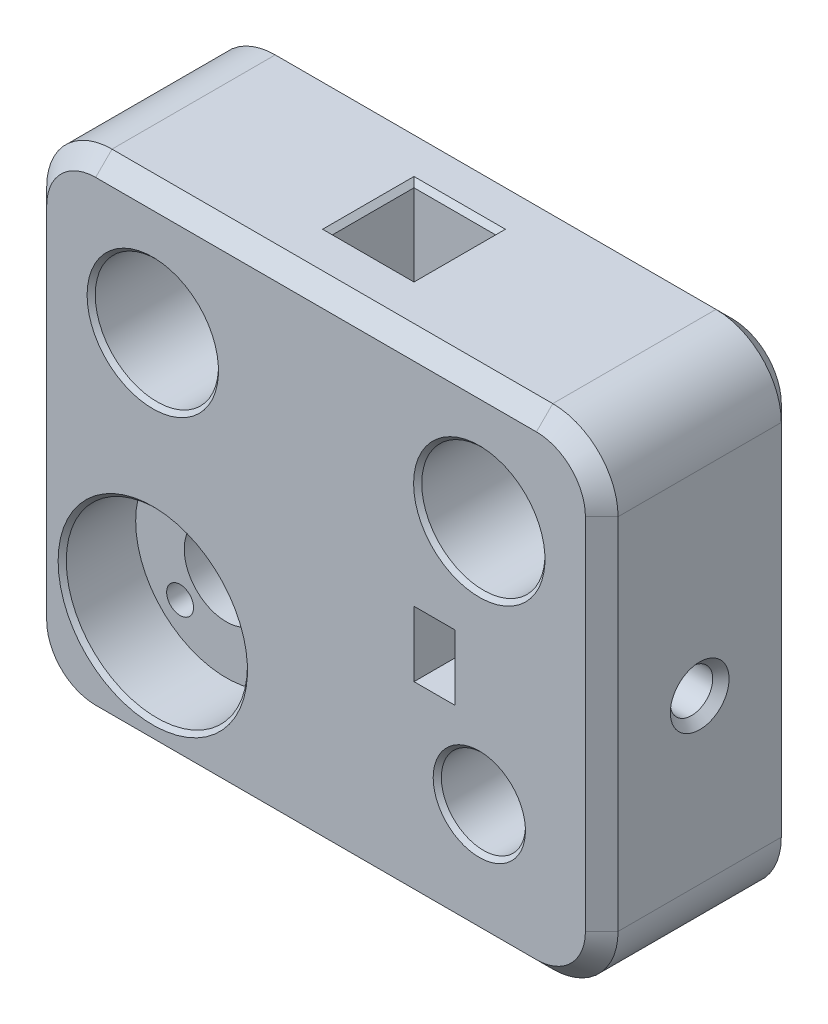
SolidWorks part; units mm, degrees
ref_plane "Front Plane" through (0, 0, 0) normal (0, 0, 1) x (1, 0, 0)
ref_plane "Top Plane" through (0, 0, 0) normal (0, 1, 0) x (1, 0, 0)
ref_plane "Right Plane" through (0, 0, 0) normal (1, 0, 0) x (0, 0, -1)
sketch "Sketch1" plane through (0, 0, 0) normal (0, 0, 1) x (1, 0, 0)
  line L1 (27, -30) -> (-27, -30)
  line L2 (35, -22) -> (35, 22)
  line L3 (27, 30) -> (-27, 30)
  line L4 (-35, -22) -> (-35, 22)
  line L5 (35, -30) -> (-35, 30) construction
  line L6 (35, 30) -> (-35, -30) construction
  line L7 (20, -15) -> (-20, -15) construction
  line L8 (20, -15) -> (20, 15) construction
  line L9 (20, 15) -> (-20, 15) construction
  line L10 (-20, -15) -> (-20, 15) construction
  line L11 (20, -15) -> (-20, 15) construction
  line L12 (20, 15) -> (-20, -15) construction
  arc A0 (-27, -30) -> (-35, -22) centre (-27, -22) cw
  arc A1 (27, -30) -> (35, -22) centre (27, -22) ccw
  arc A2 (35, 22) -> (27, 30) centre (27, 22) ccw
  arc A3 (-27, 30) -> (-35, 22) centre (-27, 22) ccw
  circle A4 centre (-20, 15) radius 7.55
  circle A5 centre (20, 15) radius 7.55
  circle A6 centre (20, -15) radius 5.15
  circle A7 centre (-20, -15) radius 5.15
  point P0 (0, 0)
  point P18 (0, 0)
  dimension "D1" = 8
  dimension "D6" = 15.1
  dimension "D7" = 10.3
  dimension "D2" = 60
  dimension "D3" = 70
  dimension "D4" = 40
  dimension "D5" = 30
extrude "Boss-Extrude1" add sketch "Sketch1" along normal mid plane 24
sketch "Sketch2" plane through (0, 0, 12) normal (0, 0, 1) x (1, 0, 0)
  circle A0 centre (-20, -15) radius 11.1
  dimension "D1" = 22.2
extrude "Cut-Extrude1" cut sketch "Sketch2" against normal blind 9
sketch "Sketch3" plane through (0, 0, 12) normal (0, 0, 1) x (1, 0, 0)
  line L1 (-25.6569, -20.6569) -> (-14.3431, -20.6569) construction
  line L2 (-25.6569, -20.6569) -> (-25.6569, -9.3431) construction
  line L3 (-25.6569, -9.3431) -> (-14.3431, -9.3431) construction
  line L4 (-14.3431, -20.6569) -> (-14.3431, -9.3431) construction
  line L5 (-25.6569, -20.6569) -> (-14.3431, -9.3431) construction
  line L6 (-25.6569, -9.3431) -> (-14.3431, -20.6569) construction
  circle A0 centre (-25.6569, -9.3431) radius 1.65
  circle A1 centre (-14.3431, -9.3431) radius 1.65
  circle A2 centre (-14.3431, -20.6569) radius 1.65
  circle A3 centre (-25.6569, -20.6569) radius 1.65
  point P0 (-20, -15)
  dimension "D2" = 3.3
  dimension "D1" = 16
extrude "Cut-Extrude2" cut sketch "Sketch3" against normal through all
sketch "Sketch4" plane through (0, 0, -12) normal (0, 0, -1) x (-1, 0, 0)
  line L0 (16.217, -11.217) -> (23.783, -18.783) construction
  line L1 (17.2988, -10.1351) -> (16.5069, -7.1794)
  line L2 (16.5069, -7.1794) -> (13.5512, -6.3875)
  line L3 (13.5512, -6.3875) -> (11.3875, -8.5512)
  line L4 (11.3875, -8.5512) -> (12.1794, -11.5069)
  line L5 (12.1794, -11.5069) -> (15.1351, -12.2988)
  line L6 (15.1351, -12.2988) -> (17.2988, -10.1351)
  line L7 (23.4931, -7.1794) -> (22.7012, -10.1351)
  line L8 (22.7012, -10.1351) -> (24.8649, -12.2988)
  line L9 (24.8649, -12.2988) -> (27.8206, -11.5069)
  line L10 (27.8206, -11.5069) -> (28.6125, -8.5512)
  line L11 (28.6125, -8.5512) -> (26.4488, -6.3875)
  line L12 (26.4488, -6.3875) -> (23.4931, -7.1794)
  line L13 (24.8649, -17.7012) -> (22.7012, -19.8649)
  line L14 (22.7012, -19.8649) -> (23.4931, -22.8206)
  line L15 (23.4931, -22.8206) -> (26.4488, -23.6125)
  line L16 (26.4488, -23.6125) -> (28.6125, -21.4488)
  line L17 (28.6125, -21.4488) -> (27.8206, -18.4931)
  line L18 (27.8206, -18.4931) -> (24.8649, -17.7012)
  line L19 (15.1351, -17.7012) -> (12.1794, -18.4931)
  line L20 (12.1794, -18.4931) -> (11.3875, -21.4488)
  line L21 (11.3875, -21.4488) -> (13.5512, -23.6125)
  line L22 (13.5512, -23.6125) -> (16.5069, -22.8206)
  line L23 (16.5069, -22.8206) -> (17.2988, -19.8649)
  line L24 (17.2988, -19.8649) -> (15.1351, -17.7012)
  line L25 (23.783, -11.217) -> (16.217, -18.783) construction
  circle A0 centre (14.3431, -9.3431) radius 2.65 construction
  circle A1 centre (25.6569, -9.3431) radius 2.65 construction
  circle A2 centre (25.6569, -20.6569) radius 2.65 construction
  circle A3 centre (14.3431, -20.6569) radius 2.65 construction
  dimension "D1" = 5.3
extrude "Cut-Extrude3" cut sketch "Sketch4" against normal blind 6
sketch "Sketch5" plane through (0, 0, 0) normal (0, 1, 0) x (1, 0, 0)
  line L1 (5, -5) -> (-5, -5)
  line L2 (5, -5) -> (5, 5)
  line L3 (5, 5) -> (-5, 5)
  line L4 (-5, -5) -> (-5, 5)
  line L5 (5, -5) -> (-5, 5) construction
  line L6 (5, 5) -> (-5, -5) construction
  point P0 (0, 0)
  dimension "D1" = 10
extrude "Cut-Extrude4" cut sketch "Sketch5" against normal through all both and the other way through all
chamfer "Chamfer1" distance 2 angle 45 16 edges at (35, 0, -12) (32.6569, 27.6569, -12) (32.6569, -27.6569, -12) (0, 30, -12) (0, -30, -12) (-32.6569, 27.6569, -12) (-32.6569, -27.6569, -12) (-35, 0, -12) (35, 0, 12) (32.6569, 27.6569, 12) (32.6569, -27.6569, 12) (0, 30, 12) (0, -30, 12) (-32.6569, 27.6569, 12) (-32.6569, -27.6569, 12) (-35, 0, 12)
chamfer "Chamfer2" distance 0.5 angle 45 7 edges at (25.15, -15, -12) (-12.45, 15, -12) (27.55, 15, -12) (25.15, -15, 12) (-8.9, -15, 12) (27.55, 15, 12) (-12.45, 15, 12)
sketch "Sketch7" plane through (35, 0, 0) normal (1, 0, 0) x (0, 0, -1)
  line L0 (0, 0) -> (0, -2) construction
  circle A0 centre (0, -2) radius 2.6
  dimension "D1" = 5.2
  dimension "D2" = 2
extrude "Cut-Extrude6" cut sketch "Sketch7" against normal blind 33
sketch "Sketch8" plane through (0, 0, 0) normal (0, 0, 1) x (1, 0, 0)
  line L0 (0, -2) -> (14.5, -2) construction
  line L1 (0, 0) -> (0, -2) construction
  line L2 (12, -6) -> (17, -6)
  line L3 (12, -6) -> (12, 2)
  line L4 (12, 2) -> (17, 2)
  line L5 (17, -6) -> (17, 2)
  line L6 (12, -6) -> (17, 2) construction
  line L7 (12, 2) -> (17, -6) construction
  dimension "D1" = 8
  dimension "D2" = 5
  dimension "D3" = 12
  dimension "D4" = 2
extrude "Cut-Extrude7" cut sketch "Sketch8" against normal through all both and the other way through all
chamfer "Chamfer3" distance 1 angle 45 1 edges at (35, -2, -2.6)
chamfer "Chamfer4" distance 0.6 angle 45 8 edges at (0, 30, -5) (-5, 30, 0) (0, 30, 5) (5, 30, 0) (0, -30, -5) (5, -30, 0) (0, -30, 5) (-5, -30, 0)
sketch "Sketch9" plane through (0, -30, 0) normal (0, -1, 0) x (1, 0, 0)
  line L0 (0, -7) -> (19, -7) construction
  line L1 (20, -9.15) -> (18, -9.15)
  line L2 (20, -9.15) -> (20, -4.85)
  line L3 (20, -4.85) -> (18, -4.85)
  line L4 (18, -9.15) -> (18, -4.85)
  line L5 (20, -9.15) -> (18, -4.85) construction
  line L6 (20, -4.85) -> (18, -9.15) construction
  line L7 (0, 0) -> (0, -7) construction
  point P0 (19, -7)
  dimension "D1" = 4.3
  dimension "D2" = 19
  dimension "D3" = 2
  dimension "D4" = 7
extrude "Cut-Extrude8" cut sketch "Sketch9" against normal blind 8
